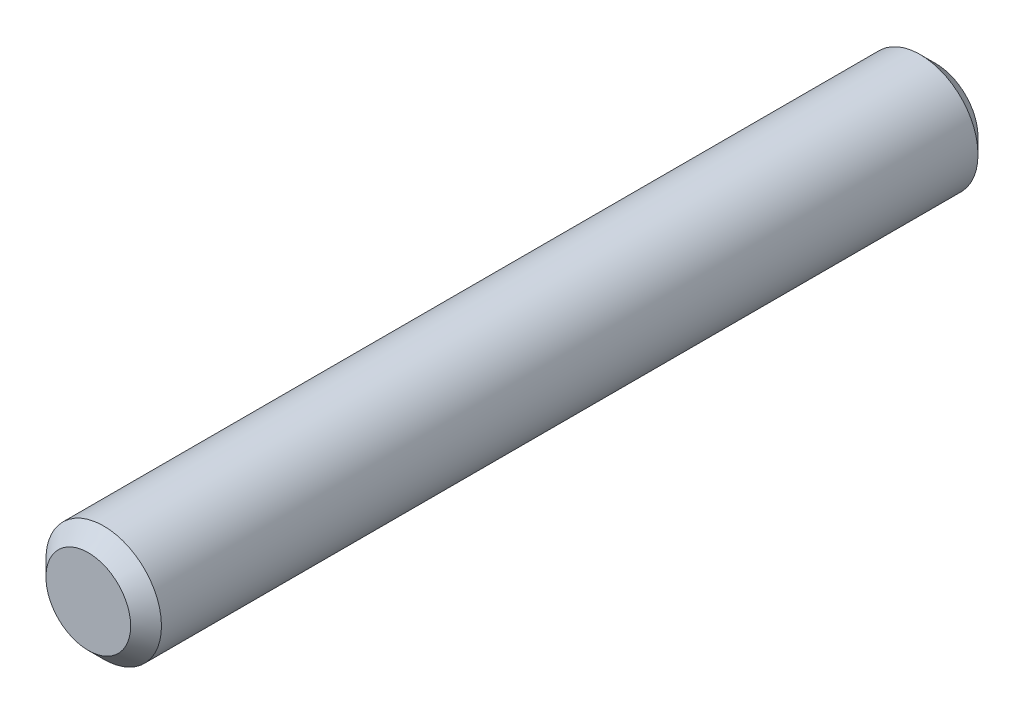
SolidWorks part; units mm, degrees
ref_plane "Front Plane" through (0, 0, 0) normal (0, 0, 1) x (1, 0, 0)
ref_plane "Top Plane" through (0, 0, 0) normal (0, 1, 0) x (1, 0, 0)
ref_plane "Right Plane" through (0, 0, 0) normal (1, 0, 0) x (0, 0, -1)
sketch "Sketch1" plane through (0, 0, 0) normal (0, 0, 1) x (1, 0, 0)
  circle A0 centre (0, 0) radius 7.5
  dimension "D1" = 15
extrude "Boss-Extrude1" add sketch "Sketch1" along normal blind 110
chamfer "Chamfer1" distance 2 angle 45 2 edges at (7.5, 0, 110) (7.5, 0, 0)
